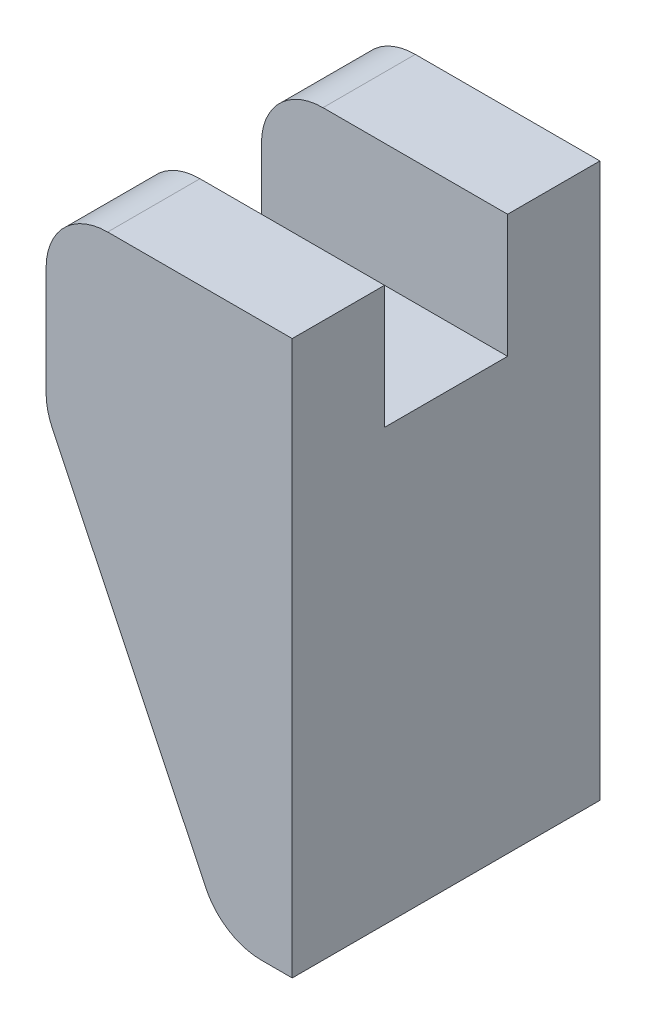
SolidWorks part; units mm, degrees
material "AISI 1020"
ref_plane "Front Plane" through (0, 0, 0) normal (0, 0, 1) x (1, 0, 0)
ref_plane "Top Plane" through (0, 0, 0) normal (0, 1, 0) x (1, 0, 0)
ref_plane "Right Plane" through (0, 0, 0) normal (1, 0, 0) x (0, 0, -1)
sketch "Sketch1" plane through (0, 0, 0) normal (0, 0, 1) x (1, 0, 0)
  line L0 (0, 45) -> (-40, 45)
  line L1 (-40, 45) -> (-40, 15)
  line L2 (-40, 15) -> (-11.3368, -45)
  line L3 (-11.3368, -45) -> (0, -45)
  line L4 (0, -45) -> (0, 45)
  point P2 (0, 0)
  dimension "D1" = 90
  dimension "D2" = 40
  dimension "D3" = 30
  dimension "D4" = 66.495
extrude "Boss-Extrude1" add sketch "Sketch1" along normal mid plane 50
sketch "Sketch2" plane through (0, 45, 0) normal (0, 1, 0) x (1, 0, 0)
  line L0 (0, -25) -> (0, 25) construction
  line L1 (-40, -10) -> (0, -10)
  line L2 (-40, -10) -> (-40, 10)
  line L3 (-40, 10) -> (0, 10)
  line L4 (0, -10) -> (0, 10)
  line L5 (-40, -10) -> (0, 10) construction
  line L6 (-40, 10) -> (0, -10) construction
  line L7 (-40, -25) -> (-40, 25) construction
  point P0 (-20, 0)
  dimension "D1" = 20
extrude "Cut-Extrude1" cut sketch "Sketch2" against normal blind 20
fillet "Fillet1" radius 10 2 edges at (-40, 45, 17.5) (-40, 45, -17.5)
fillet "Fillet2" radius 10 2 edges at (-11.3368, -45, 0) (-40, 15, 0)
